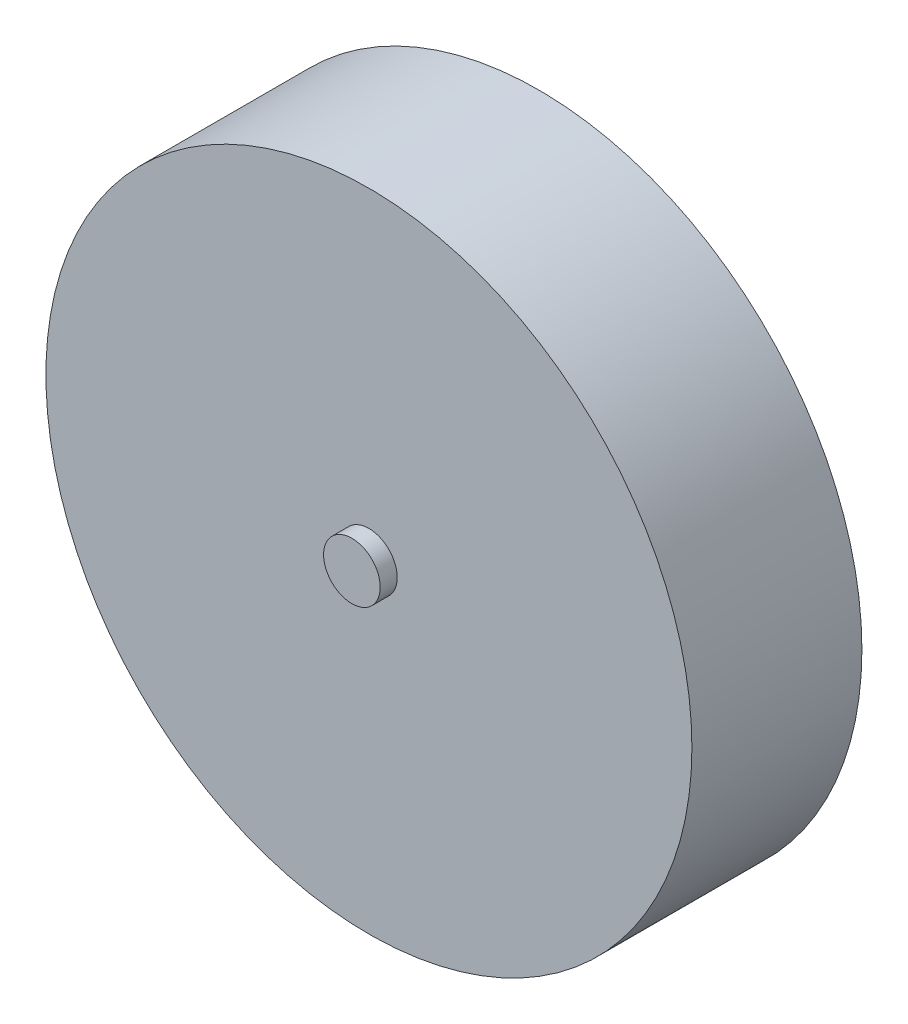
SolidWorks part; units mm, degrees
ref_plane "Plan de face" through (0, 0, 0) normal (0, 0, 1) x (1, 0, 0)
ref_plane "Plan de dessus" through (0, 0, 0) normal (0, 1, 0) x (1, 0, 0)
ref_plane "Plan de droite" through (0, 0, 0) normal (1, 0, 0) x (0, 0, -1)
sketch "Esquisse1" plane through (0, 0, 0) normal (0, 0, 1) x (1, 0, 0)
  circle A0 centre (0, 0) radius 2.85
extrude "Boss.-Extru.2" add sketch "Esquisse1" along normal blind 1.5
sketch "Esquisse3" plane through (0, 0, 1.5) normal (0, 0, 1) x (1, 0, 0)
  circle A0 centre (0, 0) radius 0.25
extrude "Boss.-Extru.4" add sketch "Esquisse3" along normal blind 0.15
